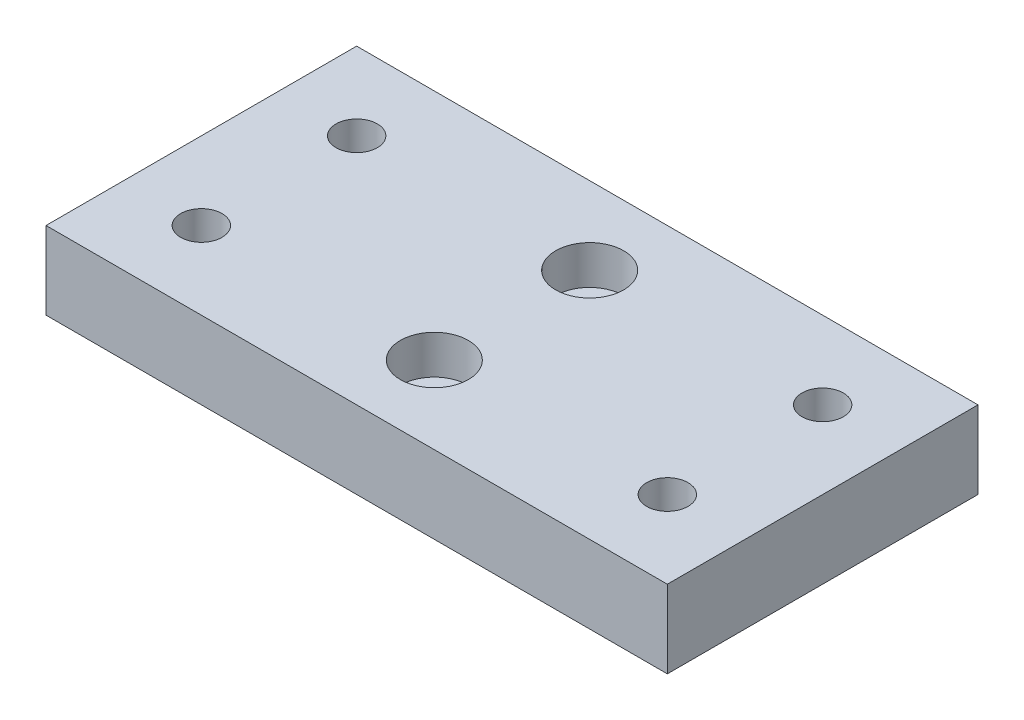
SolidWorks part; units mm, degrees
ref_plane "Front" through (0, 0, 0) normal (0, 0, 1) x (1, 0, 0)
ref_plane "Top" through (0, 0, 0) normal (0, 1, 0) x (1, 0, 0)
ref_plane "Right" through (0, 0, 0) normal (1, 0, 0) x (0, 0, -1)
sketch "Sketch1" plane through (0, 0, 0) normal (0, 1, 0) x (1, 0, 0)
  line L1 (-50.8, -25.4) -> (50.8, -25.4)
  line L2 (-50.8, -25.4) -> (-50.8, 25.4)
  line L3 (-50.8, 25.4) -> (50.8, 25.4)
  line L4 (50.8, -25.4) -> (50.8, 25.4)
  line L5 (-50.8, -25.4) -> (50.8, 25.4) construction
  line L6 (-50.8, 25.4) -> (50.8, -25.4) construction
  point P0 (0, 0)
  point P6 (0, 0)
  dimension "D1" = 101.6
  dimension "D2" = 50.8
extrude "Boss-Extrude1" add sketch "Sketch1" along normal mid plane 12.7 contours L3 L4 L1 L2
sketch "Sketch2" plane through (0, 6.35, 0) normal (0, 1, 0) x (1, 0, 0)
  line L0 (-38.1, 12.7) -> (38.1, 12.7) construction
  line L1 (38.1, 12.7) -> (38.1, -12.7) construction
  line L2 (0, -50) -> (0, 50) construction
  line L3 (-50, 0) -> (50, 0) construction
  point P2 (0, 12.7)
  point P6 (38.1, 0)
  point P9 (-38.1, -12.7)
  point P10 (0, 0)
  point P11 (0, 0)
  dimension "D1" = 76.2
  dimension "D2" = 25.4
hole_wizard "1/4 Clearance Hole1" positions "Sketch5" profile "Sketch6" hole size "1/4" standard "ANSI Inch" end condition up to next
sketch "Sketch5" plane through (0, 6.35, 0) normal (0, 1, 0) x (1, 0, 0)
  point P0 (-38.1, 12.7)
  point P3 (-38.1, -12.7)
  point P6 (38.1, 12.7)
  point P9 (38.1, -12.7)
sketch "Sketch6" plane through (-38.1, 6.35, -12.7) normal (1, 0, 0) x (0, 0, 1)
  line L0 (0, 0) -> (0, 12.7)
  line L1 (0, 12.7) -> (3.3782, 12.7)
  line L2 (3.3782, 12.7) -> (3.3782, 0)
  line L5 (3.3782, 0) -> (0, 0)
  line L11 (0, -6.35) -> (0, 107.95) construction
  dimension "Thru Hole Dia." = 6.7564
  dimension "Thru Hole Depth" = 12.7
sketch "Sketch7" plane through (0, 6.35, 0) normal (0, 1, 0) x (1, 0, 0)
  line L0 (0, -50) -> (0, 50) construction
  line L1 (0, 12.7) -> (0, -12.7) construction
  line L2 (-50, 0) -> (50, 0) construction
  point P0 (0, 12.7)
  point P1 (0, -12.7)
  point P6 (0, 42.3686)
  point P7 (0, 0)
  dimension "D1" = 25.4
hole_wizard "CBORE for 1/4 Socket Head Cap Screw1" positions "Sketch8" profile "Sketch10" counterbore size "1/4" standard "ANSI Inch" end condition through all
sketch "Sketch8" plane through (0, 6.35, 0) normal (0, 1, 0) x (1, 0, 0)
  point P0 (0, 12.7)
  point P3 (0, -12.7)
sketch "Sketch10" plane through (0, 6.35, -12.7) normal (1, 0, 0) x (0, 0, 1)
  line L0 (0, 0) -> (0, 12.7)
  line L1 (0, 12.7) -> (3.3782, 12.7)
  line L3 (3.3782, 12.7) -> (3.3782, 6.35)
  line L4 (3.3782, 6.35) -> (5.5562, 6.35)
  line L5 (5.5562, 6.35) -> (5.5562, 0)
  line L7 (5.5562, 0) -> (0, 0)
  line L11 (0, -6.35) -> (0, 107.95) construction
  dimension "Thru Hole Dia." = 6.7564
  dimension "Thru Hole Depth" = 12.7
  dimension "C'Bore Dia." = 11.1125
  dimension "C'Bore Depth" = 6.35
